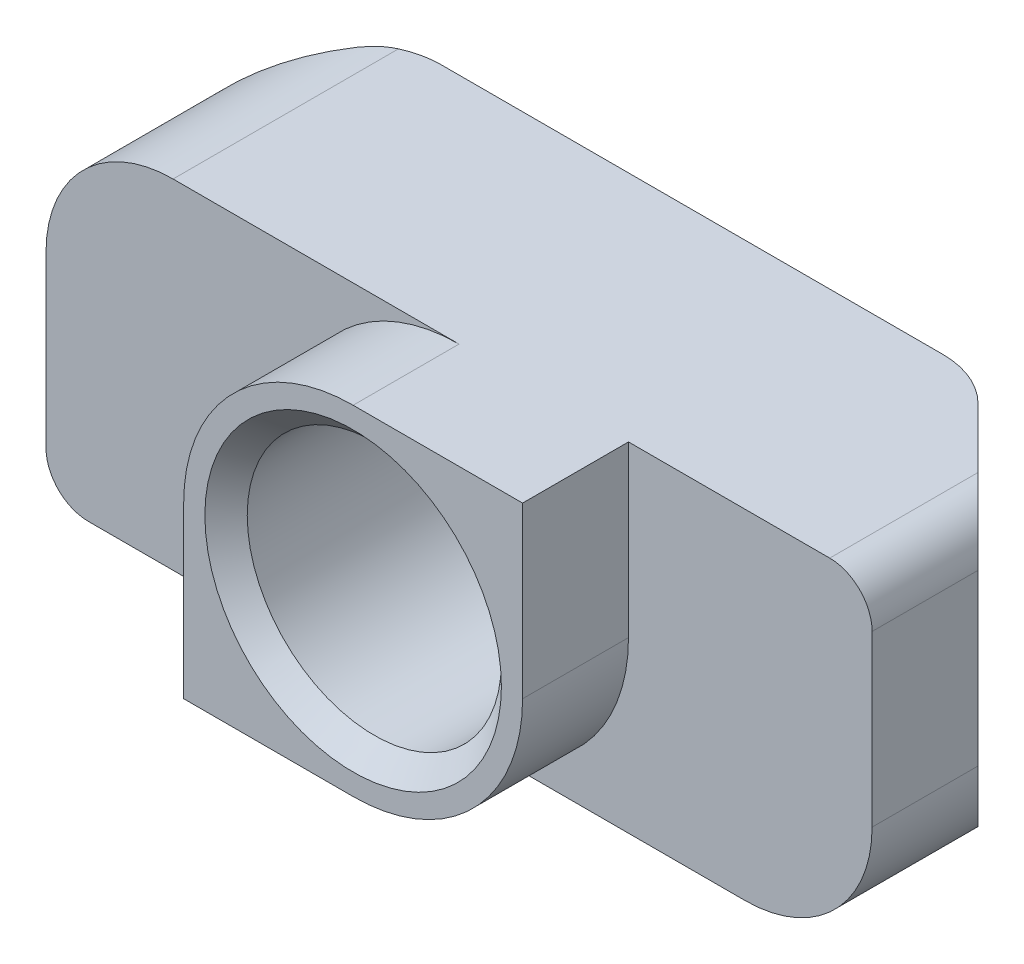
SolidWorks part; units mm, degrees
ref_plane "前视基准面" through (0, 0, 0) normal (0, 0, 1) x (1, 0, 0)
ref_plane "上视基准面" through (0, 0, 0) normal (0, 1, 0) x (1, 0, 0)
ref_plane "右视基准面" through (0, 0, 0) normal (1, 0, 0) x (0, 0, -1)
other "Configuration Table"
ref_plane "基准面1" through (0, 4, 0) normal (0, 1, 0) x (1, 0, 0)
sketch "草图1" plane through (0, 4, 0) normal (0, 1, 0) x (1, 0, 0)
  line L0 (-9.75, -3) -> (-9.75, -8)
  line L1 (-9.75, -8) -> (9.75, -8)
  line L2 (9.75, -8) -> (9.75, -3)
  line L3 (9.75, -3) -> (6.75, 0)
  line L4 (6.75, 0) -> (-6.75, 0)
  line L5 (-6.75, 0) -> (-9.75, -3)
extrude "凸台-拉伸1" add sketch "草图1" against normal blind 8
sketch "草图2" plane through (0, -4, 0) normal (0, -1, 0) x (1, 0, 0)
  line L0 (-9.75, 5.5) -> (-4, 5.5)
  line L1 (-4, 5.5) -> (-4, 8)
  line L2 (-4, 8) -> (-9.75, 8)
  line L3 (-9.75, 8) -> (-9.75, 5.5)
extrude "切除-拉伸1" cut sketch "草图2" against normal through all
sketch "草图3" plane through (0, -4, 0) normal (0, -1, 0) x (1, 0, 0)
  line L0 (4, 8) -> (4, 5.5)
  line L1 (4, 5.5) -> (9.75, 5.5)
  line L2 (9.75, 5.5) -> (9.75, 8)
  line L3 (9.75, 8) -> (4, 8)
extrude "切除-拉伸2" cut sketch "草图3" against normal through all
hole_wizard "Ø6.0 (6) 直径孔1" positions "草图5" profile "草图4" hole size "Ø6.0" standard "ANSI Metric"
sketch "草图5" plane through (0, 0, 0) normal (0, 0, -1) x (-1, 0, 0)
  point P0 (0, 0)
sketch "草图4" plane through (0, 0, 0) normal (1, 0, 0) x (0, 1, 0)
  line L0 (0, 0) -> (0, 8)
  line L1 (0, 8) -> (3, 8)
  line L2 (3, 8) -> (3, 0)
  line L5 (3, 0) -> (0, 0)
  line L11 (0, -6.35) -> (0, 107.95) construction
  dimension "通孔孔直径" = 6
  dimension "通孔孔深度" = 8
chamfer "倒角1" distance 0.5 angle 45 2 edges at (-3, 0, 8) (-3, 0, 0)
fillet "圆角1" radius 1 2 edges at (9.75, 4, 4.25) (-9.75, -4, 4.25)
fillet "圆角2" radius 2 2 edges at (6.75, 0, 0) (-6.75, 0, 0)
fillet "圆角3" radius 3 2 edges at (9.75, -4, 4.25) (-9.75, 4, 4.25)
fillet "圆角4" radius 4 2 edges at (-4, 4, 6.75) (4, -4, 6.75)
